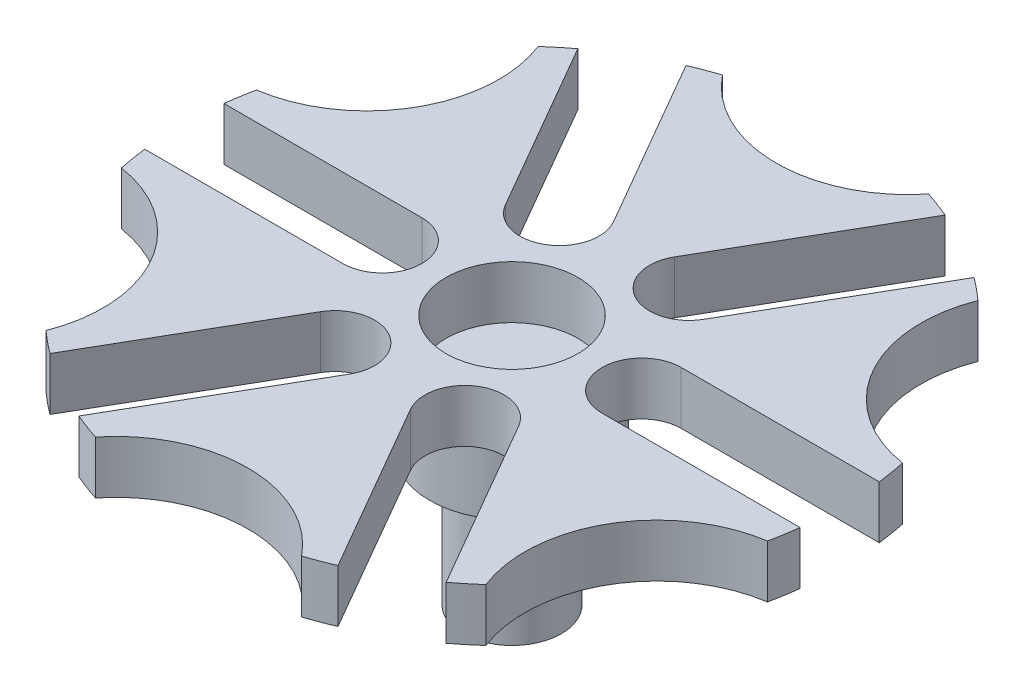
SolidWorks part; units mm, degrees
ref_plane "Front Plane" through (0, 0, 0) normal (0, 0, 1) x (1, 0, 0)
ref_plane "Top Plane" through (0, 0, 0) normal (0, 1, 0) x (1, 0, 0)
ref_plane "Right Plane" through (0, 0, 0) normal (1, 0, 0) x (0, 0, -1)
sketch "Sketch1" plane through (0, 0, 0) normal (0, 1, 0) x (1, 0, 0)
  line L13 (-19.64, -6) -> (-49.6387, -6)
  line L15 (-19.64, 6) -> (-49.6387, 6)
  line L18 (-15.0162, 14.0087) -> (-30.0155, 39.9884)
  line L20 (-4.6238, 20.0087) -> (-19.6232, 45.9884)
  line L22 (4.6238, 20.0087) -> (19.6232, 45.9884)
  line L24 (15.0162, 14.0087) -> (30.0155, 39.9884)
  line L26 (19.64, 6) -> (49.6387, 6)
  line L28 (19.64, -6) -> (49.6387, -6)
  line L30 (15.0162, -14.0087) -> (30.0155, -39.9884)
  line L32 (4.6238, -20.0087) -> (19.6232, -45.9884)
  line L34 (-4.6238, -20.0087) -> (-19.6232, -45.9884)
  line L36 (-15.0162, -14.0087) -> (-30.0155, -39.9884)
  arc A0 (-15.6125, 47.5) -> (-19.6232, 45.9884) centre (0, 0) ccw
  circle A1 centre (0, 0) radius 10
  arc A2 (15.6125, -47.5) -> (-15.6125, -47.5) centre (0, -60) ccw
  arc A3 (-33.33, -37.2708) -> (-48.9425, -10.2292) centre (-51.9615, -30) ccw
  arc A4 (-48.9425, 10.2292) -> (-33.33, 37.2708) centre (-51.9615, 30) ccw
  arc A5 (-15.6125, 47.5) -> (15.6125, 47.5) centre (0, 60) ccw
  arc A6 (33.33, 37.2708) -> (48.9425, 10.2292) centre (51.9615, 30) ccw
  arc A7 (48.9425, -10.2292) -> (33.33, -37.2708) centre (51.9615, -30) ccw
  arc A8 (-15.0162, 14.0087) -> (-4.6238, 20.0087) centre (-9.82, 17.0087) ccw
  arc A9 (33.33, 37.2708) -> (30.0155, 39.9884) centre (0, 0) ccw
  arc A10 (4.6238, 20.0087) -> (15.0162, 14.0087) centre (9.82, 17.0087) ccw
  arc A11 (48.9425, -10.2292) -> (49.6387, -6) centre (0, 0) ccw
  arc A12 (19.64, 6) -> (19.64, -6) centre (19.64, 0) ccw
  arc A13 (15.0162, -14.0087) -> (4.6238, -20.0087) centre (9.82, -17.0087) ccw
  arc A14 (-4.6238, -20.0087) -> (-15.0162, -14.0087) centre (-9.82, -17.0087) ccw
  arc A15 (-33.33, -37.2708) -> (-30.0155, -39.9884) centre (0, 0) ccw
  arc A16 (-48.9425, 10.2292) -> (-49.6387, 6) centre (0, 0) ccw
  arc A17 (-30.0155, 39.9884) -> (-33.33, 37.2708) centre (0, 0) ccw
  arc A18 (19.6232, 45.9884) -> (15.6125, 47.5) centre (0, 0) ccw
  arc A19 (49.6387, 6) -> (48.9425, 10.2292) centre (0, 0) ccw
  arc A20 (30.0155, -39.9884) -> (33.33, -37.2708) centre (0, 0) ccw
  arc A21 (15.6125, -47.5) -> (19.6232, -45.9884) centre (0, 0) ccw
  arc A22 (-19.6232, -45.9884) -> (-15.6125, -47.5) centre (0, 0) ccw
  arc A23 (-19.64, -6) -> (-19.64, 6) centre (-19.64, 0) ccw
  arc A24 (-49.6387, -6) -> (-48.9425, -10.2292) centre (0, 0) ccw
  point P61 (0, 0)
  dimension "D1" = 6
  dimension "D2" = 6
  dimension "D4" = 20
  dimension "D6" = 50
  dimension "D3" = 29.9987
  dimension "D5" = 60
extrude "Boss-Extrude1" add sketch "Sketch1" against normal blind 8
sketch "Sketch2" plane through (0, -8, 0) normal (0, -1, 0) x (1, 0, 0)
  circle A0 centre (0, 0) radius 12.5
extrude "Boss-Extrude2" add sketch "Sketch2" along normal blind 10
sketch "Sketch3" plane through (0, -18, 0) normal (0, -1, 0) x (1, 0, 0)
  circle A0 centre (0, 0) radius 7.5
extrude "Boss-Extrude3" add sketch "Sketch3" along normal blind 20
